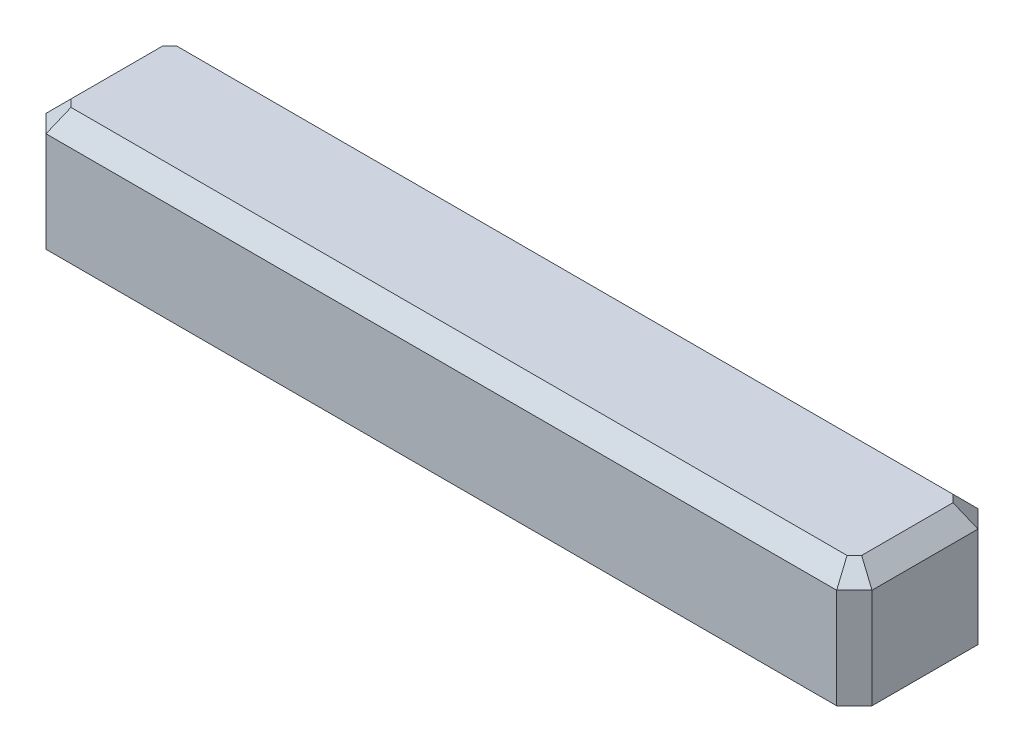
SolidWorks part; units mm, degrees
ref_plane "Front Plane" through (0, 0, 0) normal (0, 0, 1) x (1, 0, 0)
ref_plane "Top Plane" through (0, 0, 0) normal (0, 1, 0) x (1, 0, 0)
ref_plane "Right Plane" through (0, 0, 0) normal (1, 0, 0) x (0, 0, -1)
sketch "Sketch1" plane through (0, 0, 0) normal (0, 1, 0) x (1, 0, 0)
  line L0 (-35.07, 4.5) -> (-33.57, 6)
  line L1 (-33.57, -6) -> (33.57, -6)
  line L2 (-35.07, -4.5) -> (-35.07, 4.5)
  line L3 (-33.57, 6) -> (33.57, 6)
  line L4 (35.07, -4.5) -> (35.07, 4.5)
  line L5 (-35.07, -6) -> (35.07, 6) construction
  line L6 (-35.07, 6) -> (35.07, -6) construction
  line L7 (33.57, 6) -> (35.07, 4.5)
  line L8 (-35.07, -4.5) -> (-33.57, -6)
  line L9 (33.57, -6) -> (35.07, -4.5)
  point P0 (0, 0)
  point P10 (0, 0)
  dimension "D1" = 70.14
  dimension "D2" = 12
extrude "Boss-Extrude1" add sketch "Sketch1" along normal blind 10
chamfer "Chamfer1" distance 1.5 angle 45 8 edges at (-35.07, 10, 0) (0, 10, -6) (35.07, 10, 0) (0, 10, 6) (-34.32, 10, 5.25) (-34.32, 10, -5.25) (34.32, 10, -5.25) (34.32, 10, 5.25)
sketch "Sketch2" plane through (0, 0, 0) normal (0, -1, 0) x (1, 0, 0)
  line L0 (33.57, -6) -> (-33.57, -6) construction
  line L1 (-30.67, 0.8) -> (30.67, 0.8)
  line L2 (-30.67, 0.8) -> (-30.67, -3)
  line L3 (-30.67, -3) -> (30.67, -3)
  line L4 (30.67, 0.8) -> (30.67, -3)
  line L5 (-30.67, 0.8) -> (30.67, -3) construction
  line L6 (-30.67, -3) -> (30.67, 0.8) construction
  line L7 (35.07, 4.5) -> (35.07, -4.5) construction
  line L8 (-35.07, -4.5) -> (-35.07, 4.5) construction
  point P4 (0, -1.1)
  point P9 (30.67, -1.1)
  dimension "D1" = 3
  dimension "D2" = 4.4
  dimension "D3" = 4.4
  dimension "D4" = 3.8
extrude "Cut-Extrude1" cut sketch "Sketch2" against normal blind 7
